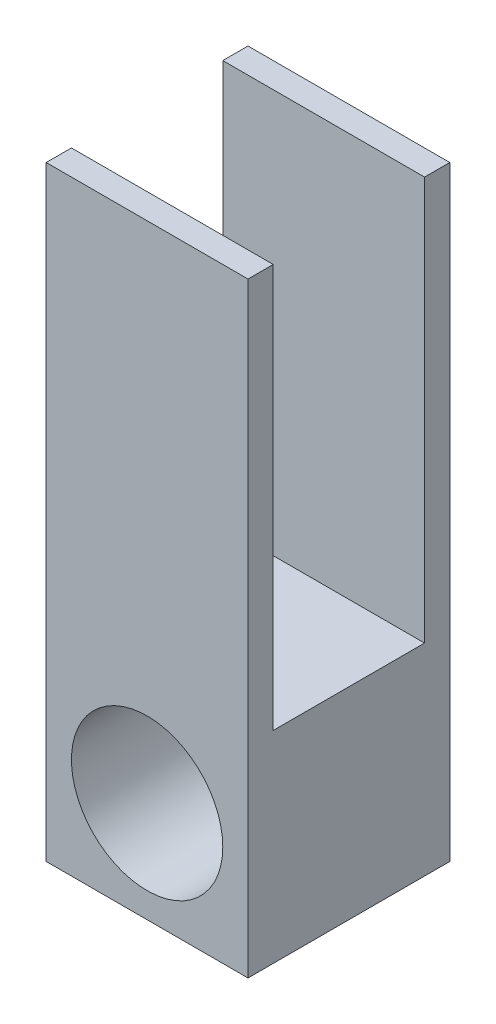
SolidWorks part; units mm, degrees
ref_plane "Front Plane" through (0, 0, 0) normal (0, 0, 1) x (1, 0, 0)
ref_plane "Top Plane" through (0, 0, 0) normal (0, 1, 0) x (1, 0, 0)
ref_plane "Right Plane" through (0, 0, 0) normal (1, 0, 0) x (0, 0, -1)
sketch "Sketch2" plane through (0, 0, 0) normal (0, 0, 1) x (1, 0, 0)
  line L1 (-3, -9) -> (3, -9)
  line L2 (-3, -9) -> (-3, 9)
  line L3 (-3, 9) -> (3, 9)
  line L4 (3, -9) -> (3, 9)
  line L5 (-3, -9) -> (3, 9) construction
  line L6 (-3, 9) -> (3, -9) construction
  point P0 (0, 0)
  dimension "D1" = 6
  dimension "D2" = 18
extrude "Boss-Extrude1" add sketch "Sketch2" along normal blind 6
sketch "Sketch3" plane through (0, 0, 6) normal (0, 0, 1) x (1, 0, 0)
  line L0 (-3, -9) -> (3, -9) construction
  circle A0 centre (0, -6) radius 2.25
  dimension "D1" = 3
extrude "Cut-Extrude1" cut sketch "Sketch3" against normal through all
sketch "Sketch4" plane through (3, 0, 0) normal (1, 0, 0) x (0, 0, -1)
  line L0 (-6, 9) -> (0, 9) construction
  line L1 (-5.25, -3) -> (-0.75, -3)
  line L2 (-5.25, -3) -> (-5.25, 9)
  line L3 (-5.25, 9) -> (-0.75, 9)
  line L4 (-0.75, -3) -> (-0.75, 9)
  line L5 (-5.25, -3) -> (-0.75, 9) construction
  line L6 (-5.25, 9) -> (-0.75, -3) construction
  line L7 (0, -9) -> (0, 9) construction
  point P0 (-3, 3)
  dimension "D1" = 4.5
  dimension "D2" = 0.75
  dimension "D3" = 12
extrude "Cut-Extrude2" cut sketch "Sketch4" against normal through all
